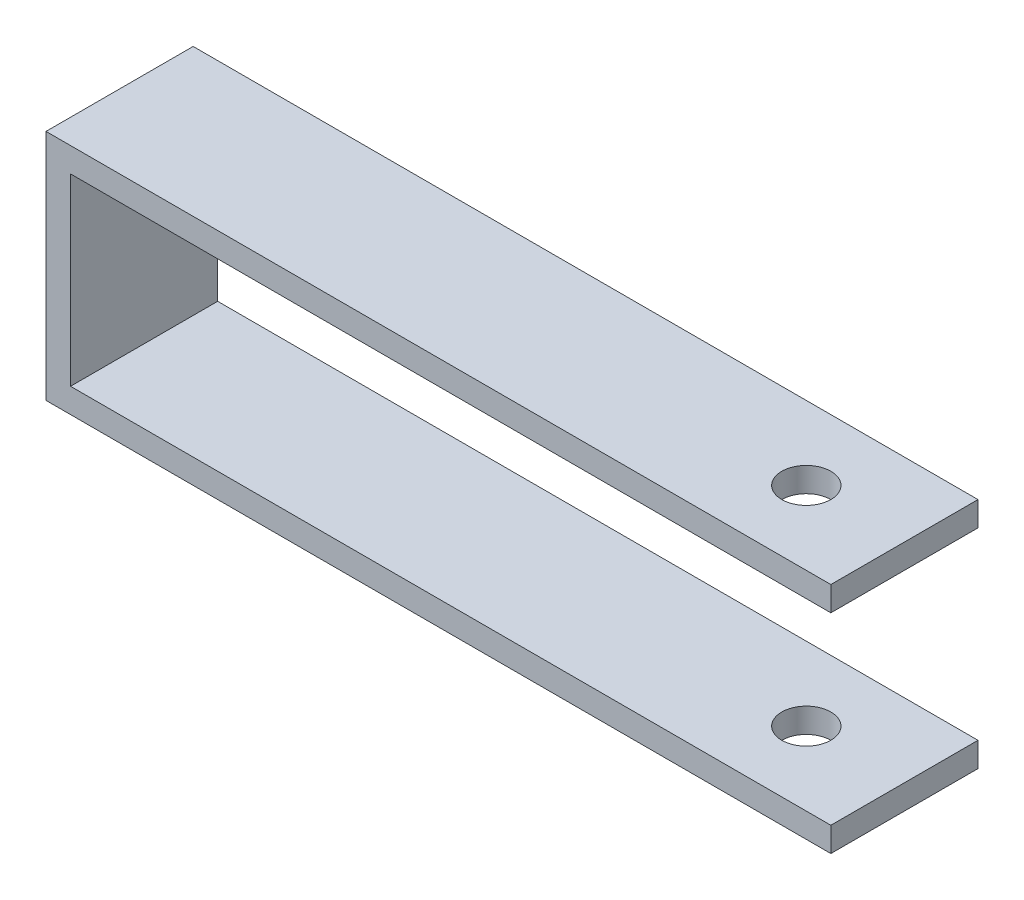
SolidWorks part; units mm, degrees
ref_plane "Front Plane" through (0, 0, 0) normal (0, 0, 1) x (1, 0, 0)
ref_plane "Top Plane" through (0, 0, 0) normal (0, 1, 0) x (1, 0, 0)
ref_plane "Right Plane" through (0, 0, 0) normal (1, 0, 0) x (0, 0, -1)
sketch "Sketch1" plane through (0, 0, 0) normal (0, 1, 0) x (1, 0, 0)
  line L1 (-155.5426, 35.2175) -> (-53.9426, 35.2175)
  line L2 (-155.5426, 35.2175) -> (-155.5426, 16.1675)
  line L3 (-155.5426, 16.1675) -> (-53.9426, 16.1675)
  line L4 (-53.9426, 35.2175) -> (-53.9426, 16.1675)
  dimension "D1" = 19.05
  dimension "D2" = 101.6
extrude "Boss-Extrude1" add sketch "Sketch1" along normal blind 3.175
sketch "Sketch5" plane through (0, 3.175, 0) normal (0, 1, 0) x (1, 0, 0)
  line L0 (-53.9426, 16.1675) -> (-53.9426, 35.2175) construction
  line L1 (-53.9426, 35.2175) -> (-155.5426, 35.2175) construction
  circle A0 centre (-66.6426, 25.6925) radius 3.175
  dimension "D1" = 6.35
  dimension "D2" = 12.7
  dimension "D3" = 9.525
extrude "Cut-Extrude2" cut sketch "Sketch5" against normal through all
ref_plane "Plane1" through (0, 26.9875, 0) normal (0, 1, 0) x (1, 0, 0)
sketch "Sketch6" plane through (0, 26.9875, 0) normal (0, 1, 0) x (1, 0, 0)
  line L1 (-155.5426, 35.2175) -> (-53.9426, 35.2175)
  line L2 (-155.5426, 35.2175) -> (-155.5426, 16.1675)
  line L3 (-155.5426, 16.1675) -> (-53.9426, 16.1675)
  line L4 (-53.9426, 35.2175) -> (-53.9426, 16.1675)
  circle A0 centre (-66.6426, 25.6925) radius 3.175
extrude "Boss-Extrude2" add sketch "Sketch6" along normal blind 3.175 separate body
sketch "Sketch9" plane through (-155.5426, 0, 0) normal (-1, 0, 0) x (0, 0, 1)
  line L0 (-35.2175, 0) -> (-16.1675, 0) construction
  line L1 (-16.1675, 30.1625) -> (-35.2175, 30.1625)
  line L2 (-16.1675, 30.1625) -> (-16.1675, 0)
  line L3 (-16.1675, 0) -> (-35.2175, 0)
  line L4 (-35.2175, 30.1625) -> (-35.2175, 0)
  dimension "D1" = 19.05
extrude "Boss-Extrude5" add sketch "Sketch9" against normal blind 3.175
